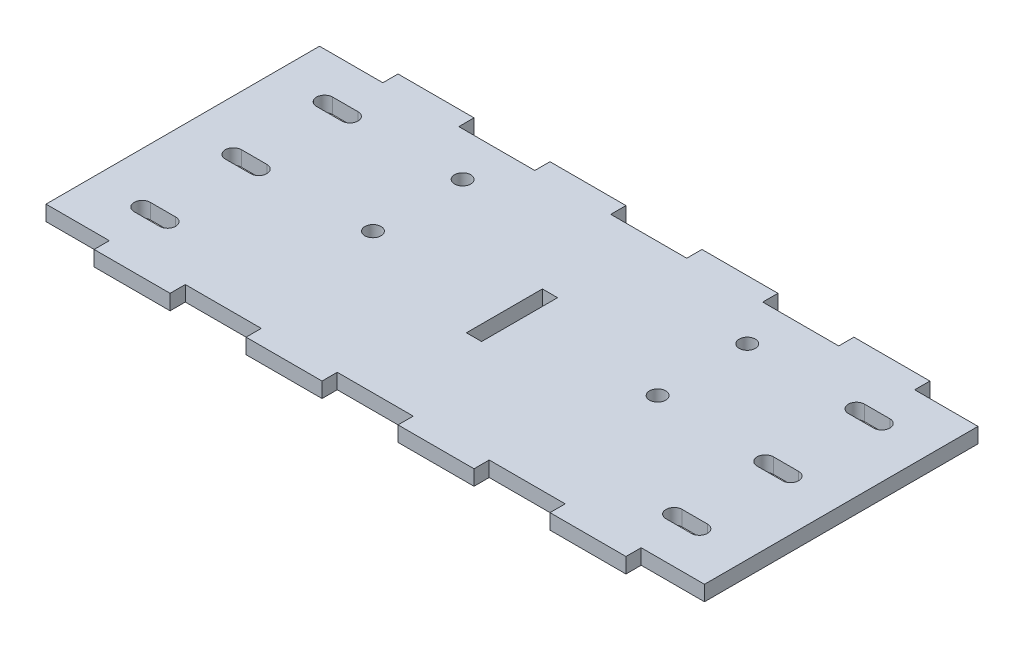
SolidWorks part; units mm, degrees
material "ABS PC"
ref_plane "Front Plane" through (0, 0, 0) normal (0, 0, 1) x (1, 0, 0)
ref_plane "Top Plane" through (0, 0, 0) normal (0, 1, 0) x (1, 0, 0)
ref_plane "Right Plane" through (0, 0, 0) normal (1, 0, 0) x (0, 0, -1)
sketch "Sketch1" plane through (0, 0, 0) normal (0, 1, 0) x (1, 0, 0)
  line L0 (-65, 27) -> (-52.5, 27)
  line L1 (-52.5, 27) -> (-52.5, 30)
  line L2 (-52.5, 30) -> (-37.5, 30)
  line L3 (-37.5, 30) -> (-37.5, 27)
  line L4 (-37.5, 27) -> (-22.5, 27)
  line L5 (-22.5, 27) -> (-22.5, 30)
  line L6 (-22.5, 30) -> (-7.5, 30)
  line L7 (-7.5, 30) -> (-7.5, 27)
  line L8 (-7.5, 27) -> (7.5, 27)
  line L9 (0, 27) -> (0, 0) construction
  line L10 (0, 0) -> (0, -27) construction
  line L11 (7.5, -27) -> (-7.5, -27)
  line L12 (-7.5, -27) -> (-7.5, -30)
  line L13 (-7.5, -30) -> (-22.5, -30)
  line L14 (-22.5, -30) -> (-22.5, -27)
  line L15 (-22.5, -27) -> (-37.5, -27)
  line L16 (-37.5, -27) -> (-37.5, -30)
  line L17 (-37.5, -30) -> (-52.5, -30)
  line L18 (-52.5, -30) -> (-52.5, -27)
  line L19 (-52.5, -27) -> (-65, -27)
  line L20 (-65, -27) -> (-65, 27)
  line L21 (-7.5, 27) -> (7.5, 27) construction
  line L22 (7.5, 30) -> (7.5, 27)
  line L23 (22.5, 30) -> (7.5, 30)
  line L24 (22.5, 27) -> (22.5, 30)
  line L25 (37.5, 27) -> (22.5, 27)
  line L26 (37.5, 30) -> (37.5, 27)
  line L27 (52.5, 30) -> (37.5, 30)
  line L28 (52.5, 27) -> (52.5, 30)
  line L29 (65, 27) -> (52.5, 27)
  line L30 (65, -27) -> (65, 27)
  line L31 (52.5, -27) -> (65, -27)
  line L32 (52.5, -30) -> (52.5, -27)
  line L33 (37.5, -30) -> (52.5, -30)
  line L34 (37.5, -27) -> (37.5, -30)
  line L35 (22.5, -27) -> (37.5, -27)
  line L36 (22.5, -30) -> (22.5, -27)
  line L37 (7.5, -30) -> (22.5, -30)
  line L38 (7.5, -27) -> (7.5, -30)
  dimension "D1" = 15
  dimension "D2" = 60
  dimension "D3" = 3
  dimension "D4" = 130
extrude "Boss-Extrude1" add sketch "Sketch1" along normal blind 3
sketch "Sketch2" plane through (0, 3, 0) normal (0, 1, 0) x (1, 0, 0)
  line L0 (-55, 0) -> (-50, 0) construction
  line L1 (-55, 1.6) -> (-50, 1.6)
  line L2 (-55, -1.6) -> (-50, -1.6)
  line L3 (55, 0) -> (50, 0) construction
  line L4 (55, 1.6) -> (50, 1.6)
  line L5 (55, -1.6) -> (50, -1.6)
  line L6 (-52.5, 0) -> (-65, 0) construction
  line L7 (-65, 27) -> (-65, -27) construction
  line L8 (55, 18) -> (50, 18) construction
  line L10 (-55, 18) -> (-50, 18) construction
  line L11 (-55, 19.6) -> (-50, 19.6)
  line L12 (-55, 16.4) -> (-50, 16.4)
  line L13 (-55, -18) -> (-50, -18) construction
  line L14 (-55, -16.4) -> (-50, -16.4)
  line L15 (-55, -19.6) -> (-50, -19.6)
  line L16 (-52.5, -18) -> (-52.5, 0) construction
  line L17 (-52.5, 0) -> (-52.5, 18) construction
  line L18 (-37.5, 30) -> (-52.5, 30) construction
  line L19 (0, 27) -> (0, 0) construction
  line L20 (7.5, 27) -> (-7.5, 27) construction
  line L21 (55, 19.6) -> (50, 19.6)
  line L22 (55, 16.4) -> (50, 16.4)
  line L23 (55, -18) -> (50, -18) construction
  line L24 (55, -16.4) -> (50, -16.4)
  line L25 (55, -19.6) -> (50, -19.6)
  line L26 (52.5, 0) -> (52.5, 18) construction
  line L27 (52.5, -18) -> (52.5, 0) construction
  arc A0 (-55, 1.6) -> (-55, -1.6) centre (-55, 0) ccw
  arc A1 (-50, -1.6) -> (-50, 1.6) centre (-50, 0) ccw
  arc A2 (55, 1.6) -> (55, -1.6) centre (55, 0) cw
  arc A3 (50, -1.6) -> (50, 1.6) centre (50, 0) cw
  arc A4 (-55, 19.6) -> (-55, 16.4) centre (-55, 18) ccw
  arc A5 (-50, 16.4) -> (-50, 19.6) centre (-50, 18) ccw
  arc A6 (-55, -16.4) -> (-55, -19.6) centre (-55, -18) ccw
  arc A7 (-50, -19.6) -> (-50, -16.4) centre (-50, -18) ccw
  arc A8 (55, 19.6) -> (55, 16.4) centre (55, 18) cw
  arc A9 (50, 16.4) -> (50, 19.6) centre (50, 18) cw
  arc A10 (55, -16.4) -> (55, -19.6) centre (55, -18) cw
  arc A11 (50, -19.6) -> (50, -16.4) centre (50, -18) cw
  point P2 (-52.5, 0)
  point P9 (52.5, 0)
  point P21 (52.5, 18)
  point P25 (-52.5, 18)
  point P30 (-52.5, -18)
  point P50 (52.5, -18)
  dimension "D2" = 1.6
  dimension "D1" = 12.5
  dimension "D3" = 5
  dimension "D4" = 12
extrude "Cut-Extrude1" cut sketch "Sketch2" against normal through all
sketch "Sketch3" plane through (0, 3, 0) normal (0, 1, 0) x (1, 0, 0)
  line L0 (0, 7.5) -> (0, 0) construction
  line L1 (-1.5, 7.5) -> (1.5, 7.5)
  line L2 (-1.5, 7.5) -> (-1.5, -7.5)
  line L3 (-1.5, -7.5) -> (1.5, -7.5)
  line L4 (1.5, 7.5) -> (1.5, -7.5)
  line L5 (0, 0) -> (0, -7.5) construction
  dimension "D1" = 3
  dimension "D2" = 15
extrude "Cut-Extrude2" cut sketch "Sketch3" against normal through all
sketch "Sketch4" plane through (0, 0, 0) normal (0, -1, 0) x (1, 0, 0)
  circle A0 centre (-28.1, -0.65) radius 1.6
  circle A1 centre (-28.1, -0.65) radius 1.3 construction
  circle A2 centre (-28.1, -18.35) radius 1.6
  circle A3 centre (-28.1, -18.35) radius 1.3 construction
  dimension "D3" = 3.2
extrude "Cut-Extrude3" cut sketch "Sketch4" against normal through all
mirror "Mirror1" about plane through (0, 0, 0) normal (1, 0, 0) of "Cut-Extrude3"
